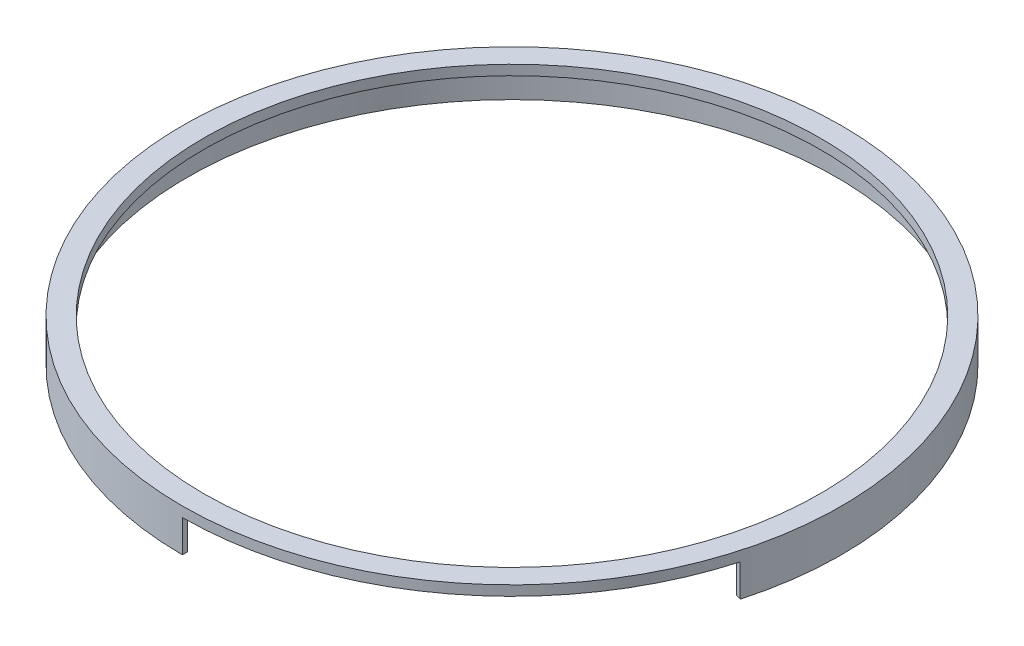
SolidWorks part; units mm, degrees
ref_plane "Front Plane" through (0, 0, 0) normal (0, 0, 1) x (1, 0, 0)
ref_plane "Top Plane" through (0, 0, 0) normal (0, 1, 0) x (1, 0, 0)
ref_plane "Right Plane" through (0, 0, 0) normal (1, 0, 0) x (0, 0, -1)
sketch "Sketch2" plane through (0, 0, 0) normal (0, 1, 0) x (1, 0, 0)
  circle A0 centre (0, 0) radius 62
  circle A1 centre (0, 0) radius 66.3
  dimension "D1" = 124
  dimension "D2" = 132.6
extrude "Boss-Extrude1" add sketch "Sketch2" along normal blind 2
sketch "Sketch3" plane through (0, 0, 0) normal (0, -1, 0) x (1, 0, 0)
  line L0 (0, 0) -> (0, 66.3) construction
  line L1 (63.8328, 17.9182) -> (62.87, 17.6479)
  line L2 (0, 65.3) -> (0, 66.3)
  circle A0 centre (0, 0) radius 65.3
  circle A2 centre (0, 0) radius 66.3 construction
  circle A3 centre (0, 0) radius 66.3
  arc A4 (0, 66.3) -> (63.8328, 17.9182) centre (0, 0) cw
  circle M1 centre (0, 0) radius 66.3
  dimension "D1" = 1
  dimension "D2" = 86
extrude "Boss-Extrude2" add sketch "Sketch3" along normal blind 6.5 contours A0 L2 L1 M1
sketch "Sketch4" plane through (0, 0, 0) normal (0, -1, 0) x (1, 0, 0)
  line L0 (0, 66.3) -> (0, 65.3)
  line L1 (63.8328, 17.9182) -> (62.87, 17.6479)
  arc A0 (63.8328, 17.9182) -> (0, 66.3) centre (0, 0) ccw
  arc A1 (0, 65.3) -> (62.87, 17.6479) centre (0, 0) cw
